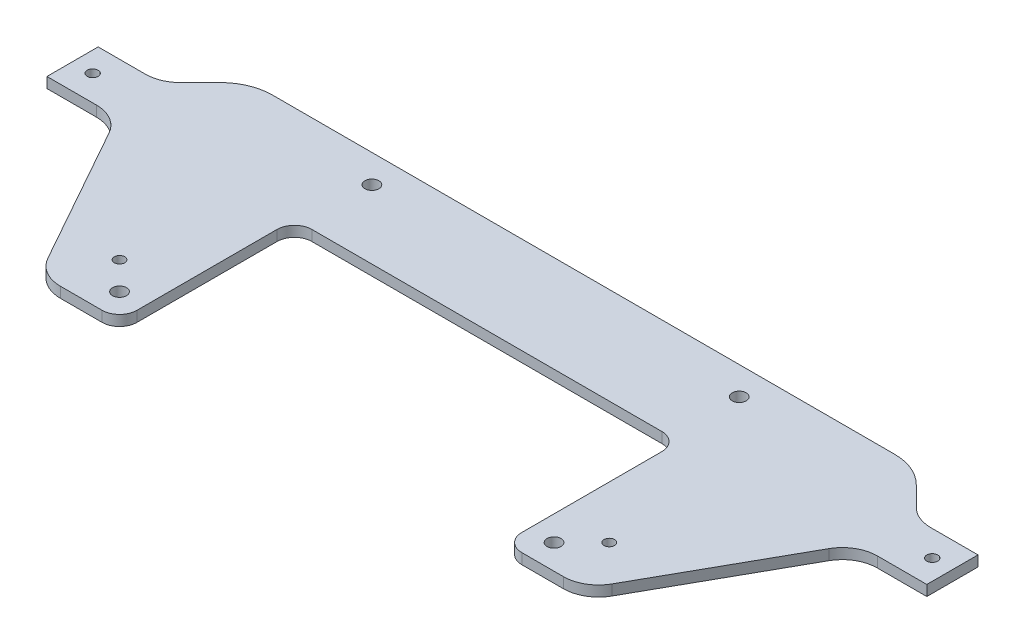
SolidWorks part; units mm, degrees
ref_plane "Alzado" through (0, 0, 0) normal (0, 0, 1) x (1, 0, 0)
ref_plane "Planta" through (0, 0, 0) normal (0, 1, 0) x (1, 0, 0)
ref_plane "Vista lateral" through (0, 0, 0) normal (1, 0, 0) x (0, 0, -1)
sketch "Croquis1" plane through (0, 0, 0) normal (0, 1, 0) x (1, 0, 0)
  line L0 (-27.8825, 0) -> (38.5584, 0) construction
  line L1 (-88.1, 42.3182) -> (88.1, 42.3182)
  line L2 (-77.75, -42.3182) -> (77.75, -42.3182)
  line L3 (-88.1, 42.3182) -> (-108.1, 22.3182)
  line L4 (-108.1, 22.3182) -> (-127.75, 22.3182)
  line L5 (0, 0) -> (0, 27.7067) construction
  line L6 (-127.75, 22.3182) -> (-127.75, 7.6818)
  line L7 (-127.75, 7.6818) -> (-105.75, 7.6818)
  line L8 (-105.75, 7.6818) -> (-77.75, -42.3182)
  line L9 (88.1, 42.3182) -> (108.1, 22.3182)
  line L10 (108.1, 22.3182) -> (127.75, 22.3182)
  line L11 (127.75, 22.3182) -> (127.75, 7.6818)
  line L12 (127.75, 7.6818) -> (105.75, 7.6818)
  line L13 (105.75, 7.6818) -> (77.75, -42.3182)
  dimension "D1" = 255.5
  dimension "D2" = 84.6363
  dimension "D3" = 19.65
  dimension "D4" = 22
  dimension "D5" = 22
  dimension "D6" = 50
  dimension "D7" = 50
  dimension "D8" = 50
  dimension "D9" = 20
  dimension "D10" = 20
extrude "Saliente-Extruir1" add sketch "Croquis1" along normal blind 3
fillet "Redondeo1" radius 10 8 edges at (88.1, 1.5, -42.3182) (-88.1, 1.5, -42.3182) (-77.75, 1.5, 42.3182) (77.75, 1.5, 42.3182) (108.1, 1.5, -22.3182) (105.75, 1.5, -7.6818) (-105.75, 1.5, -7.6818) (-108.1, 1.5, -22.3182)
sketch "Croquis2" plane through (0, 3, 0) normal (0, 1, 0) x (1, 0, 0)
  line L0 (0, 0) -> (0, -87.7887) construction
  line L1 (-119.9961, 22.3182) -> (-119.9961, 40.4374) construction
  line L2 (-112.2421, 22.3182) -> (-127.75, 22.3182) construction
  line L3 (-127.75, 15) -> (-123.2915, 15) construction
  line L4 (-127.75, 22.3182) -> (-127.75, 7.6818) construction
  line L5 (119.9961, 22.3182) -> (119.9961, 29.1715) construction
  line L6 (127.75, 22.3182) -> (112.2421, 22.3182) construction
  line L7 (115.6048, 15) -> (126.3231, 15) construction
  line L10 (-71.8888, -42.3182) -> (71.8888, -42.3182) construction
  circle A0 centre (70, -27.3182) radius 1.5
  circle A1 centre (-70, -27.3182) radius 1.5
  circle A2 centre (-119.9961, 15) radius 1.55
  circle A3 centre (119.9961, 15) radius 1.55
  circle A6 centre (-17.5, -17.3182) radius 1.5
  circle A7 centre (17.5, -17.3182) radius 1.5
  circle A8 centre (-17.5, -37.3182) radius 1.5
  circle A9 centre (17.5, -37.3182) radius 1.5
  dimension "D1" = 3.1
  dimension "D2" = 3.1
  dimension "D10" = 3
  dimension "D11" = 3
  dimension "D17" = 3
  dimension "D18" = 3
  dimension "D19" = 3
  dimension "D20" = 3
  dimension "D9" = 140
  dimension "D12" = 15
  dimension "D13" = 35
  dimension "D14" = 35
  dimension "D15" = 5
  dimension "D16" = 20
extrude "Cortar-Extruir1" cut sketch "Croquis2" against normal through all
sketch "Croquis4" plane through (0, 3, 0) normal (0, 1, 0) x (1, 0, 0)
  line L0 (-55, -42.3182) -> (-55, 7.6818)
  line L1 (-55, 7.6818) -> (55, 7.6818)
  line L2 (55, 7.6818) -> (55, -42.3182)
  line L3 (55, -42.3182) -> (-55, -42.3182)
  line L4 (0, 0) -> (0, 21.6247) construction
  line L5 (-71.8888, -42.3182) -> (71.8888, -42.3182) construction
  dimension "D1" = 110
  dimension "D2" = 50
extrude "Cortar-Extruir2" cut sketch "Croquis4" against normal through all
fillet "Redondeo2" radius 5 4 edges at (-55, 1.5, 42.3182) (55, 1.5, 42.3182) (55, 1.5, -7.6818) (-55, 1.5, -7.6818)
sketch "Croquis5" plane through (0, 3, 0) normal (0, 1, 0) x (1, 0, 0)
  line L0 (-127.75, 22.3182) -> (-127.75, 7.6818)
  line L1 (-127.75, 7.6818) -> (-123.75, 7.6818)
  line L2 (-127.75, 7.6818) -> (-111.6112, 7.6818) construction
  line L3 (-123.75, 7.6818) -> (-123.75, 22.3182)
  line L4 (-112.2421, 22.3182) -> (-127.75, 22.3182) construction
  line L5 (-123.75, 22.3182) -> (-127.75, 22.3182)
  line L6 (127.75, 22.3182) -> (127.75, 7.6818)
  line L7 (127.75, 7.6818) -> (123.75, 7.6818)
  line L8 (111.6112, 7.6818) -> (127.75, 7.6818) construction
  line L9 (123.75, 7.6818) -> (123.75, 22.3182)
  line L10 (127.75, 22.3182) -> (112.2421, 22.3182) construction
  line L11 (123.75, 22.3182) -> (127.75, 22.3182)
  dimension "D1" = 4
  dimension "D2" = 4
extrude "Cortar-Extruir3" cut sketch "Croquis5" against normal through all
sketch "Croquis6" plane through (123.75, 0, 0) normal (1, 0, 0) x (0, 0, -1)
  line L0 (7.6818, 3) -> (22.3182, 3)
  line L1 (22.3182, 3) -> (22.3182, 0)
  line L2 (22.3182, 0) -> (7.6818, 0)
  line L3 (22.3182, 0) -> (7.6818, 0) construction
  line L4 (7.6818, 0) -> (7.6818, 3) construction
  line L5 (7.6818, 3) -> (7.6818, 0)
extrude "Saliente-Extruir2" add sketch "Croquis6" along normal blind 2
sketch "Croquis8" plane through (-123.75, 0, 0) normal (-1, 0, 0) x (0, 0, 1)
  line L4 (-7.6818, 3) -> (-22.3182, 3)
  line L5 (-22.3182, 3) -> (-22.3182, 0)
  line L6 (-22.3182, 0) -> (-7.6818, 0)
  line L7 (-7.6818, 0) -> (-7.6818, 3)
  line L8 (-7.6818, 3) -> (-22.3182, 3)
  line L9 (-22.3182, 3) -> (-22.3182, 0)
  line L10 (-22.3182, 0) -> (-7.6818, 0)
  line L11 (-7.6818, 0) -> (-7.6818, 3)
  dimension "D1" = 0
extrude "Saliente-Extruir3" add sketch "Croquis8" along normal blind 2
sketch "Croquis9" plane through (0, 3, 0) normal (0, 1, 0) x (1, 0, 0)
  line L7 (-98.1, 66.4057) -> (98.1, 66.4057)
  line L8 (98.1, 66.4057) -> (98.1, 35.3182)
  line L9 (0, 0) -> (0, 90.0009) construction
  line L15 (-98.1, 66.4057) -> (-98.1, 35.3182)
  line L16 (-98.1, 35.3182) -> (98.1, 35.3182)
  line L17 (83.9579, 42.3182) -> (-83.9579, 42.3182) construction
  dimension "D1" = 7
extrude "Cortar-Extruir4" cut sketch "Croquis9" against normal through all
fillet "Redondeo3" [suppressed] radius 50
sketch "Croquis10" plane through (0, 3, 0) normal (0, 1, 0) x (1, 0, 0)
  line L0 (0, 0) -> (0, 30.8751) construction
  line L2 (-95.1, 35.3182) -> (95.1, 35.3182) construction
  circle A0 centre (-52.5, 27.3182) radius 2
  circle A1 centre (52.5, 27.3182) radius 2
  dimension "D1" = 4
  dimension "D2" = 4
  dimension "D3" = 105
  dimension "D4" = 8
  dimension "D5" = 8
extrude "Cortar-Extruir5" cut sketch "Croquis10" against normal through all
fillet "Redondeo6" radius 15 2 edges at (95.1, 1.5, -35.3182) (-95.1, 1.5, -35.3182)
sketch "Croquis11" plane through (0, 3, 0) normal (0, 1, 0) x (1, 0, 0)
  line L0 (0, 0) -> (0, -44.254) construction
  line L1 (-71.8888, -42.3182) -> (-60, -42.3182) construction
  line L2 (-55, 2.6818) -> (-55, -37.3182) construction
  circle A0 centre (-62.1, -35.2182) radius 2
  circle A1 centre (62.1, -35.2182) radius 2
  dimension "D1" = 4
  dimension "D2" = 7.1
  dimension "D3" = 7.1
extrude "Cortar-Extruir6" cut sketch "Croquis11" against normal blind 10
